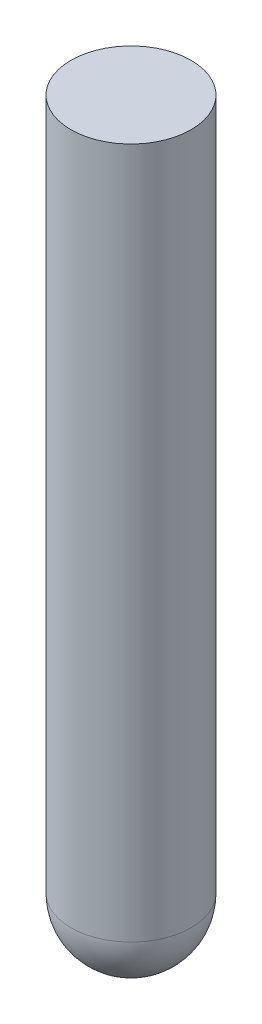
SolidWorks part; units mm, degrees
ref_plane "Front Plane" through (0, 0, 0) normal (0, 0, 1) x (1, 0, 0)
ref_plane "Top Plane" through (0, 0, 0) normal (0, 1, 0) x (1, 0, 0)
ref_plane "Right Plane" through (0, 0, 0) normal (1, 0, 0) x (0, 0, -1)
sketch "Sketch1" plane through (0, 0, 0) normal (0, 1, 0) x (1, 0, 0)
  circle A0 centre (0, 0) radius 4
  dimension "D1" = 8
extrude "Boss-Extrude1" add sketch "Sketch1" along normal blind 50
ref_point "Point1"
fillet "Fillet1" radius 4 1 edges at (0, 0, 4)
